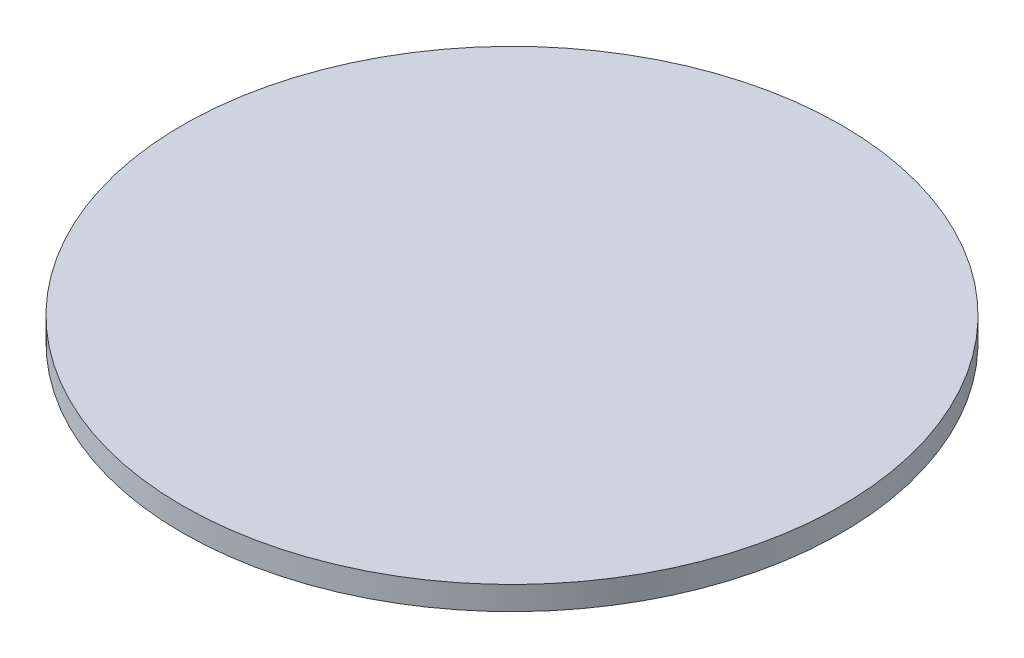
SolidWorks part; units mm, degrees
ref_plane "Front Plane" through (0, 0, 0) normal (0, 0, 1) x (1, 0, 0)
ref_plane "Top Plane" through (0, 0, 0) normal (0, 1, 0) x (1, 0, 0)
ref_plane "Right Plane" through (0, 0, 0) normal (1, 0, 0) x (0, 0, -1)
sketch "Sketch1" plane through (0, 0, 0) normal (0, 1, 0) x (1, 0, 0)
  circle A0 centre (0, 0) radius 88.9
  dimension "D1" = 177.8
extrude "Boss-Extrude1" add sketch "Sketch1" along normal blind 6.35
equation "\"od\"=7"
equation "\"D1@Sketch1\"=\"od\""
